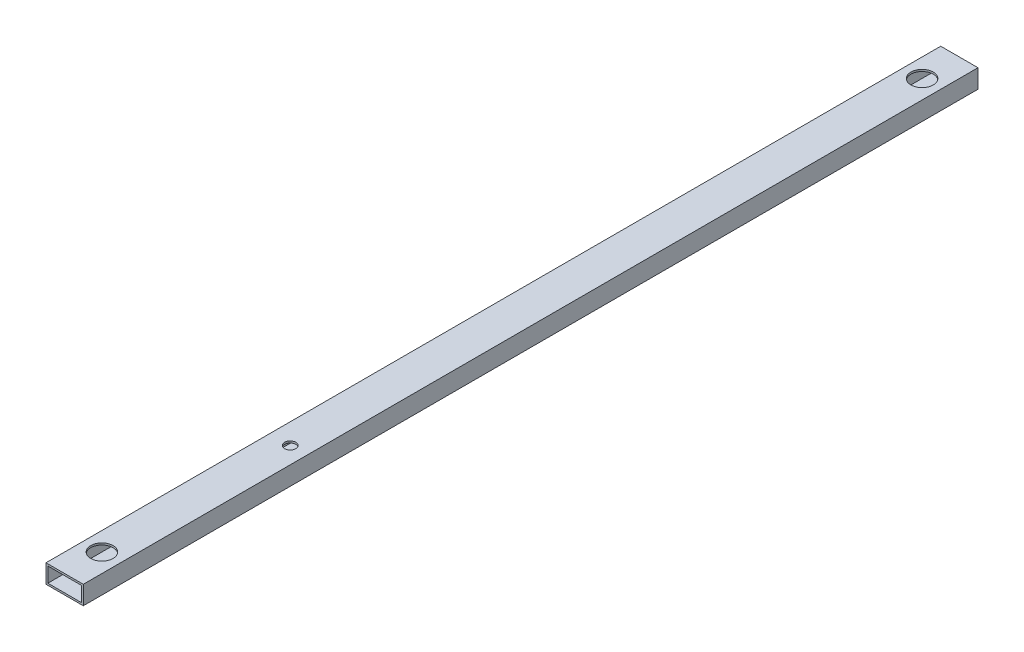
SolidWorks part; units mm, degrees
ref_plane "Front Plane" through (0, 0, 0) normal (0, 0, 1) x (1, 0, 0)
ref_plane "Top Plane" through (0, 0, 0) normal (0, 1, 0) x (1, 0, 0)
ref_plane "Right Plane" through (0, 0, 0) normal (1, 0, 0) x (0, 0, -1)
sketch "Sketch1" plane through (0, 0, 0) normal (0, 0, 1) x (1, 0, 0)
  line L1 (-21.7338, 14.3817) -> (28.2662, 14.3817)
  line L2 (-21.7338, 14.3817) -> (-21.7338, -10.6183)
  line L3 (-21.7338, -10.6183) -> (28.2662, -10.6183)
  line L4 (28.2662, 14.3817) -> (28.2662, -10.6183)
  dimension "D1" = 50
  dimension "D2" = 25
extrude "Boss-Extrude1" add sketch "Sketch1" along normal blind 1200
shell "Shell1" thickness 2.5
sketch "Sketch2" plane through (0, 0, 0) normal (0, 1, 0) x (1, 0, 0)
  line L0 (28.2662, -1200) -> (-21.7338, -1200) construction
  line L1 (28.2662, -1200) -> (28.2662, 0) construction
  circle A0 centre (5.7662, -900) radius 7.5
  dimension "D1" = 15
  dimension "D2" = 300
  dimension "D3" = 22.5
extrude "Cut-Extrude1" cut sketch "Sketch2" along normal through all both and the other way through all
sketch "Sketch3" plane through (0, 14.3817, 0) normal (0, 1, 0) x (1, 0, 0)
  line L0 (28.2662, 0) -> (-21.7338, 0) construction
  line L2 (28.2662, -1200) -> (28.2662, 0) construction
  circle A0 centre (3.2662, -50) radius 15.0011
  circle A1 centre (3.2662, -1150) radius 15.0012
  point P4 (3.2662, 0)
  dimension "D1" = 30.0023
  dimension "D2" = 25
  dimension "D3" = 2
extrude "Cut-Extrude2" cut sketch "Sketch3" against normal through all
